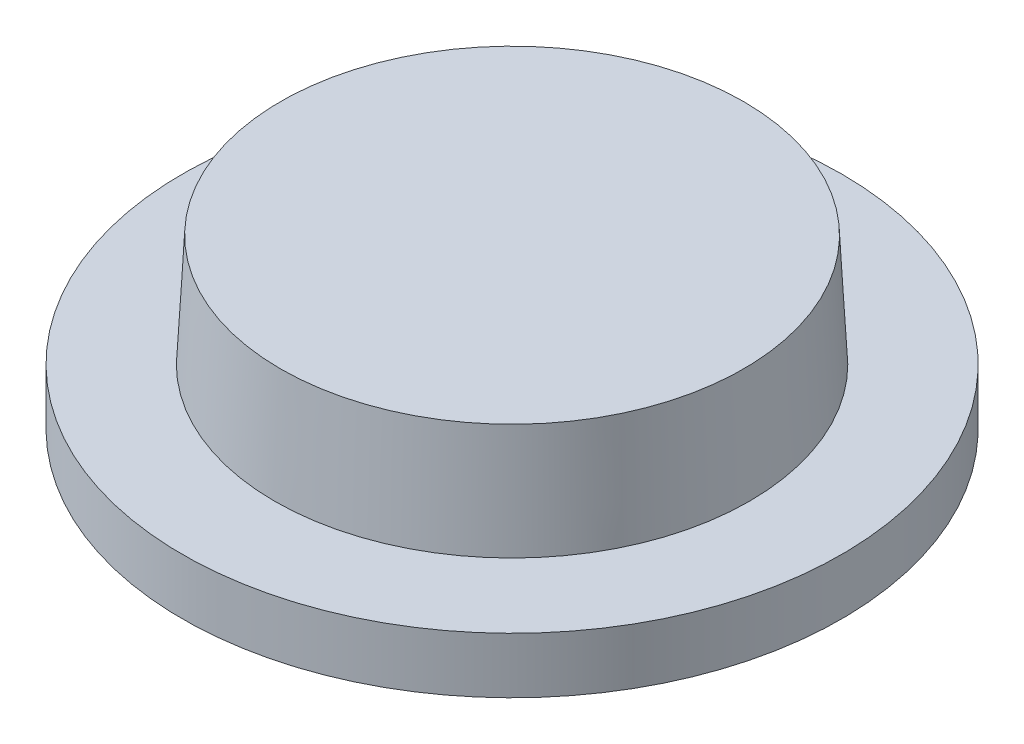
SolidWorks part; units mm, degrees
ref_plane "Front Plane" through (0, 0, 0) normal (0, 0, 1) x (1, 0, 0)
ref_plane "Top Plane" through (0, 0, 0) normal (0, 1, 0) x (1, 0, 0)
ref_plane "Right Plane" through (0, 0, 0) normal (1, 0, 0) x (0, 0, -1)
sketch "Sketch1" plane through (0, 0, 0) normal (0, 1, 0) x (1, 0, 0)
  circle A0 centre (0, 0) radius 2.125
extrude "Boss-Extrude1" add sketch "Sketch1" along normal blind 1 draft 3
sketch "Sketch2" plane through (0, 0, 0) normal (0, -1, 0) x (1, 0, 0)
  circle A0 centre (0, 0) radius 2.95
  dimension "D1" = 5.9
extrude "Boss-Extrude2" add sketch "Sketch2" along normal blind 0.5
